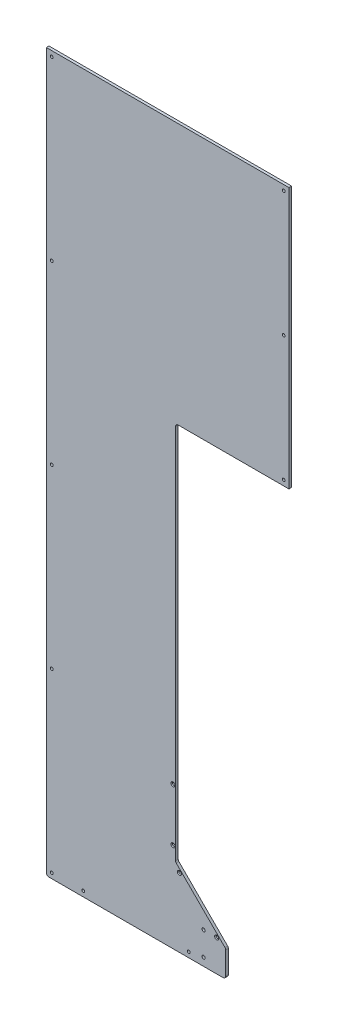
SolidWorks part; units mm, degrees
material "PC High Viscosity"
ref_plane "Front Plane" through (0, 0, 0) normal (0, 0, 1) x (1, 0, 0)
ref_plane "Top Plane" through (0, 0, 0) normal (0, 1, 0) x (1, 0, 0)
ref_plane "Right Plane" through (0, 0, 0) normal (1, 0, 0) x (0, 0, -1)
sketch "Sketch2" plane through (0, 0, 0) normal (0, 0, 1) x (1, 0, 0)
  line L1 (0, 0) -> (584.2, 0)
  line L2 (0, 0) -> (0, 1727.2)
  line L3 (0, 1727.2) -> (584.2, 1727.2)
  line L4 (584.2, 0) -> (584.2, 1727.2)
  dimension "D1" = 584.2
  dimension "D2" = 1727.2
extrude "Boss-Extrude1" add sketch "Sketch2" along normal blind 6.35
sketch "Sketch3" plane through (0, 0, 6.35) normal (0, 0, 1) x (1, 0, 0)
  line L0 (584.2, 1098.55) -> (311.15, 1098.55)
  line L1 (584.2, 0) -> (584.2, 1727.2) construction
  line L2 (311.15, 1098.55) -> (311.15, 184.15)
  line L5 (431.8, 56.7648) -> (333.3633, 155.2015) construction
  line L6 (584.2, 0) -> (431.8, 0)
  line L7 (584.2, 0) -> (584.2, 1098.55)
  line L8 (584.2, 1727.2) -> (0, 1727.2) construction
  line L9 (0, 1727.2) -> (0, 0) construction
  line L10 (311.15, 184.15) -> (431.8, 63.5)
  line L11 (431.8, 63.5) -> (431.8, 0)
  circle A0 centre (584.2, 241.3) radius 241.3 construction
  dimension "D3" = 241.3
  dimension "D5" = 482.6
  dimension "D7" = 431.8
  dimension "D1" = 628.65
  dimension "D2" = 311.15
  dimension "D4" = 584.2
  dimension "D6" = 273.05
  dimension "D8" = 63.5
  dimension "D9" = 135
  dimension "D10" = 9.525
  dimension "D11" = 56.7648
  dimension "D12" = 170.6249
extrude "Cut-Extrude1" cut sketch "Sketch3" against normal through all
sketch "Sketch4" plane through (0, 0, 6.35) normal (0, 0, 1) x (1, 0, 0)
  line L0 (0, 1727.2) -> (0, 0) construction
  line L1 (584.2, 1098.55) -> (584.2, 1727.2) construction
  line L2 (584.2, 1727.2) -> (0, 1727.2) construction
  point P0 (12.7, 1714.5)
  point P1 (12.7, 1289.05)
  point P2 (12.7, 863.6)
  point P3 (12.7, 438.15)
  point P4 (12.7, 12.7)
  point P5 (571.5, 1111.25)
  point P6 (571.5, 1412.875)
  point P7 (571.5, 1714.5)
  dimension "D1" = 12.7
  dimension "D2" = 12.7
  dimension "D3" = 12.7
  dimension "D4" = 301.625
  dimension "D5" = 603.25
  dimension "D6" = 425.45
  dimension "D7" = 425.45
  dimension "D8" = 425.45
  dimension "D9" = 425.45
hole_wizard "H (0.266) Diameter Hole1" positions "Sketch5" profile "Sketch6" hole size "H" standard "ANSI Inch" end condition through all
sketch "Sketch5" plane through (0, 0, 6.35) normal (0, 0, 1) x (1, 0, 0)
  point P0 (12.7, 1714.5)
  point P3 (12.7, 1289.05)
  point P6 (12.7, 863.6)
  point P9 (12.7, 438.15)
  point P12 (12.7, 12.7)
  point P15 (571.5, 1111.25)
  point P18 (571.5, 1412.875)
  point P21 (571.5, 1714.5)
sketch "Sketch6" plane through (12.7, 1714.5, 6.35) normal (1, 0, 0) x (0, -1, 0)
  line L0 (0, 0) -> (0, 6.35)
  line L1 (0, 6.35) -> (3.3782, 6.35)
  line L2 (3.3782, 6.35) -> (3.3782, 0)
  line L5 (3.3782, 0) -> (0, 0)
  line L11 (0, -6.35) -> (0, 107.95) construction
  dimension "Thru Hole Dia." = 6.7564
  dimension "Thru Hole Depth" = 6.35
fillet "Fillet1" radius 6.35 5 edges at (311.15, 1098.55, 3.175) (431.8, 63.5, 3.175) (311.15, 184.15, 3.175) (0, 0, 3.175) (431.8, 0, 3.175)
sketch "Sketch7" plane through (0, 0, 6.35) normal (0, 0, 1) x (1, 0, 0)
  line L0 (6.35, 0) -> (425.45, 0) construction
  line L1 (0, 1727.2) -> (0, 6.35) construction
  circle A0 centre (88.9, 12.7) radius 3.3782
  circle A1 centre (342.9, 12.7) radius 3.3782
  dimension "D1" = 12.7
  dimension "D3" = 6.7564
  dimension "D2" = 254
  dimension "D4" = 88.9
extrude "Cut-Extrude2" cut sketch "Sketch7" against normal blind 12.7
sketch "Sketch8" plane through (0, 0, 6.35) normal (0, 0, 1) x (1, 0, 0)
  line L0 (311.15, 1092.2) -> (311.15, 186.7803) construction
  line L1 (6.35, 0) -> (425.45, 0) construction
  circle A0 centre (304.8, 342.9) radius 3.3655 construction
  circle A1 centre (304.8, 215.9) radius 3.3655 construction
  point P5 (304.8, 342.9)
  point P8 (304.8, 215.9)
  dimension "D1" = 6.35
  dimension "D2" = 6.731
  dimension "D3" = 127
  dimension "D4" = 215.9
sketch "Sketch10" plane through (0, 0, 6.35) normal (0, 0, 1) x (1, 0, 0)
  line L0 (320.3172, 166.0026) -> (410.1197, 76.2) construction
  line L2 (313.0099, 182.2901) -> (429.9401, 65.3599) construction
  line L3 (6.35, 0) -> (425.45, 0) construction
  circle A0 centre (320.3172, 166.0026) radius 3.3655 construction
  circle A1 centre (410.1197, 76.2) radius 3.3655 construction
  point P9 (410.1197, 76.2)
  point P10 (320.3172, 166.0026)
  dimension "D1" = 127
  dimension "D4" = 6.731
  dimension "D2" = 76.2
  dimension "D3" = 6.35
hole_wizard "CSK for #10 Flat Head Machine Screw (100)1" positions "Sketch11" profile "Sketch12" countersink size "#10" standard "ANSI Inch" end condition up to next
sketch "Sketch11" plane through (0, 0, 6.35) normal (0, 0, 1) x (1, 0, 0)
  point P0 (304.8, 342.9)
  point P3 (304.8, 215.9)
  point P6 (320.3172, 166.0026)
  point P9 (410.1197, 76.2)
sketch "Sketch12" plane through (304.8, 342.9, 6.35) normal (1, 0, 0) x (0, -1, 0)
  line L0 (0, 0) -> (0, 6.35)
  line L1 (0, 6.35) -> (2.8067, 6.35)
  line L2 (2.8067, 6.35) -> (2.8067, 1.7477)
  line L3 (2.8067, 1.7477) -> (4.8895, 0)
  line L5 (4.8895, 0) -> (0, 0)
  line L6 (-2.8067, 1.7477) -> (-4.8895, 0) construction
  line L11 (0, -6.35) -> (0, 107.95) construction
  dimension "Thru Hole Dia." = 5.6134
  dimension "Thru Hole Depth" = 6.35
  dimension "Near C'Sink Dia." = 9.779
  dimension "Near C'Sink Angle" = 100
sketch "Sketch13" plane through (0, 0, 0) normal (0, 0, -1) x (-1, 0, 0)
  line L0 (-431.8, 6.35) -> (-431.8, 76.2) construction
  line L1 (-6.35, 0) -> (-425.45, 0) construction
  line L2 (-25.4, 0) -> (-425.45, 0) construction
  circle A0 centre (-378.4676, 76.2) radius 3.937
  circle A1 centre (-378.4676, 19.05) radius 3.937
  point P8 (0, 0)
  point P10 (-375.405, 0)
  point P14 (0, 0)
  point P15 (0, 0)
  dimension "D1" = 7.874
  dimension "D2" = 7.874
  dimension "D3" = 76.2
  dimension "D4" = 19.05
  dimension "D5" = 53.3324
extrude "Cut-Extrude3" cut sketch "Sketch13" against normal through all
